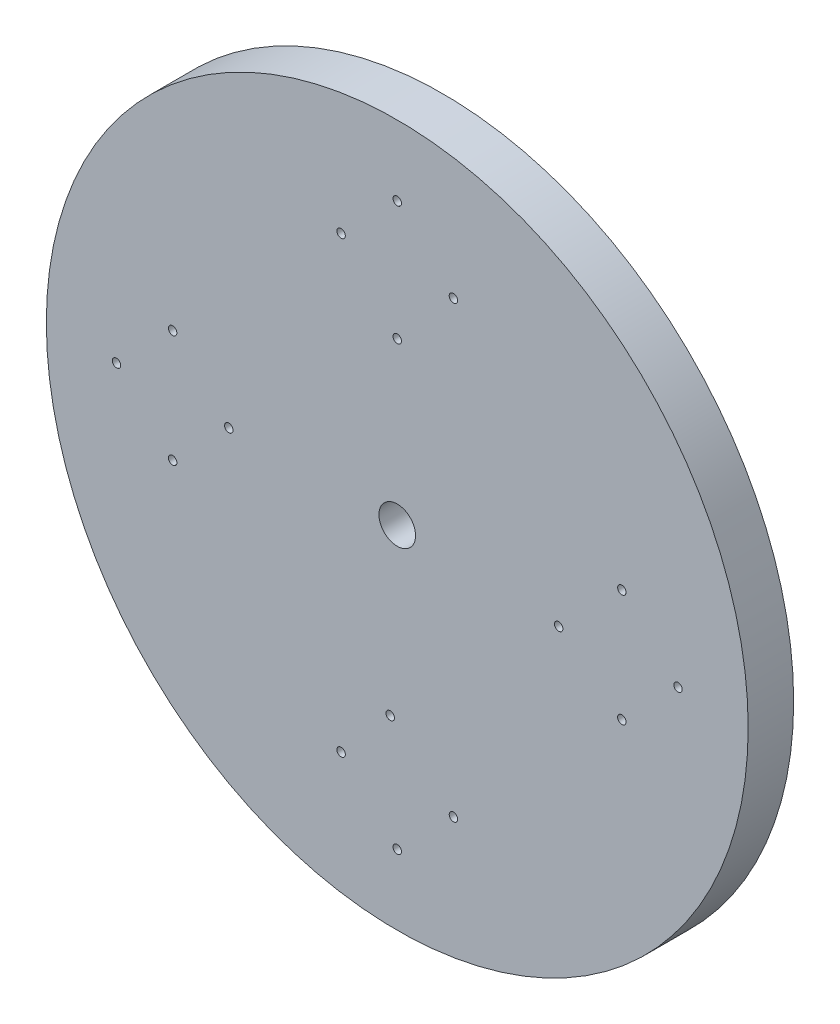
SolidWorks part; units mm, degrees
ref_plane "前视基准面" through (0, 0, 0) normal (0, 0, 1) x (1, 0, 0)
ref_plane "上视基准面" through (0, 0, 0) normal (0, 1, 0) x (1, 0, 0)
ref_plane "右视基准面" through (0, 0, 0) normal (1, 0, 0) x (0, 0, -1)
sketch "草图1" plane through (0, 0, 0) normal (0, 0, 1) x (1, 0, 0)
  circle A0 centre (0, 0) radius 125
  dimension "D1" = 250
extrude "凸台-拉伸1" add sketch "草图1" along normal mid plane 16.2
sketch "草图2" plane through (0, 0, -8.1) normal (0, 0, -1) x (-1, 0, 0)
  line L0 (0, 34.5) -> (0, -54.0093) construction
  line L1 (125, 0) -> (-43.3242, 0) construction
  circle A0 centre (0, 0) radius 34.5 construction
  circle A1 centre (0, 0) radius 125 construction
  circle A2 centre (0, 34.5) radius 1.03
  circle A3 centre (13.2026, 31.8738) radius 1.03
  circle A4 centre (24.3952, 24.3952) radius 1.03
  circle A5 centre (31.8738, 13.2026) radius 1.03
  circle A6 centre (34.5, 0) radius 1.03
  circle A7 centre (31.8738, -13.2026) radius 1.03
  circle A8 centre (24.3952, -24.3952) radius 1.03
  circle A9 centre (13.2026, -31.8738) radius 1.03
  circle A10 centre (0, -34.5) radius 1.03
  circle A11 centre (-13.2026, -31.8738) radius 1.03
  circle A12 centre (-24.3952, -24.3952) radius 1.03
  circle A13 centre (-31.8738, -13.2026) radius 1.03
  circle A14 centre (-34.5, 0) radius 1.03
  circle A15 centre (-31.8738, 13.2026) radius 1.03
  circle A16 centre (-24.3952, 24.3952) radius 1.03
  circle A17 centre (-13.2026, 31.8738) radius 1.03
  point P44 (0, 0)
  dimension "D1" = 69
  dimension "D2" = 2.06
  dimension "D3" = 16
sketch "草图3" plane through (0, 0, 8.1) normal (0, 0, 1) x (1, 0, 0)
  circle A0 centre (0, 0) radius 6.52
  dimension "D1" = 13.04
extrude "切除-拉伸1" cut sketch "草图3" against normal through all both and the other way through all
sketch "草图7" plane through (0, 0, 8.1) normal (0, 0, 1) x (1, 0, 0)
  circle A0 centre (0, 0) radius 80 construction
  circle A1 centre (0, 80) radius 20 construction
  circle A2 centre (0, 0) radius 80 construction
  circle A3 centre (80, 0) radius 20 construction
  circle A4 centre (0, 0) radius 80 construction
  circle A5 centre (0, -80) radius 20 construction
  circle A6 centre (0, 0) radius 80 construction
  circle A7 centre (-80, 0) radius 20 construction
  circle A8 centre (-100, 0) radius 1.5
  circle A9 centre (-80, 20) radius 1.5
  circle A10 centre (-60, 0) radius 1.5
  circle A11 centre (-80, -20) radius 1.5
  circle A12 centre (0, 57.5) radius 1.5
  circle A13 centre (57.5, -2.5) radius 1.5
  circle A14 centre (-2.5, -60) radius 1.5
  circle A15 centre (-20, 80) radius 1.5
  circle A16 centre (80, 20) radius 1.5
  circle A17 centre (20, -80) radius 1.5
  circle A18 centre (20, 80) radius 1.5
  circle A19 centre (0, 100) radius 1.5
  circle A20 centre (80, -20) radius 1.5
  circle A21 centre (100, 0) radius 1.5
  circle A22 centre (-20, -80) radius 1.5
  circle A23 centre (0, -100) radius 1.5
  point P17 (0, 0)
  point P26 (-80, 0)
  point P33 (-1.25, -1.25)
  point P40 (0, 0)
  point P53 (0, 0)
  dimension "D1" = 160
  dimension "D2" = 40
  dimension "D4" = 3
  dimension "D3" = 4
  dimension "D5" = 4
  dimension "D6" = 4
  dimension "D7" = 4
  dimension "D8" = 4
extrude "切除-拉伸4" cut sketch "草图2" against normal blind 10
extrude "切除-拉伸5" cut sketch "草图7" against normal blind 10
